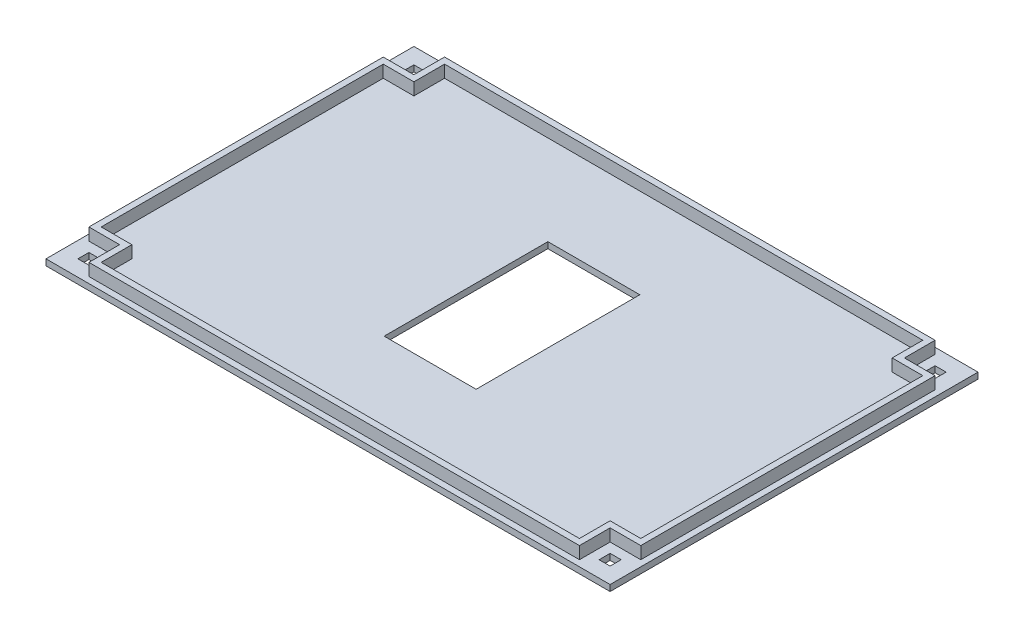
SolidWorks part; units mm, degrees
ref_plane "Спереди" through (0, 0, 0) normal (0, 0, 1) x (1, 0, 0)
ref_plane "Сверху" through (0, 0, 0) normal (0, 1, 0) x (1, 0, 0)
ref_plane "Справа" through (0, 0, 0) normal (1, 0, 0) x (0, 0, -1)
sketch "Эскиз1" plane through (0, 0, 0) normal (0, 1, 0) x (1, 0, 0)
  line L0 (0, 0) -> (92, 0)
  line L1 (0, 0) -> (0, 60)
  line L2 (0, 60) -> (92, 60)
  line L3 (92, 0) -> (92, 60)
  point P4 (0, 0)
  dimension "D1" = 60
  dimension "D2" = 92
extrude "Бобышка-Вытянуть1" add sketch "Эскиз1" along normal blind 1
sketch "Эскиз2" plane through (0, 1, 0) normal (0, 1, 0) x (1, 0, 0)
  line L0 (0, 60) -> (0, 0) construction
  line L1 (91, 1) -> (1, 1)
  line L2 (91, 1) -> (91, 59)
  line L3 (91, 59) -> (1, 59)
  line L4 (1, 1) -> (1, 59)
  line L5 (92, 60) -> (0, 60) construction
  line L6 (92, 0) -> (92, 60) construction
  line L7 (0, 0) -> (92, 0) construction
  line L8 (3.5, 4.4) -> (3.5, 2.6) construction
  line L9 (1, 59) -> (6, 59)
  line L10 (1, 59) -> (1, 54)
  line L11 (1, 54) -> (6, 54)
  line L12 (6, 59) -> (6, 54)
  line L13 (91, 59) -> (86, 59)
  line L14 (91, 59) -> (91, 54)
  line L15 (91, 54) -> (86, 54)
  line L16 (86, 59) -> (86, 54)
  line L17 (91, 1) -> (86, 1)
  line L18 (91, 1) -> (91, 6)
  line L19 (91, 6) -> (86, 6)
  line L20 (86, 1) -> (86, 6)
  line L21 (1, 1) -> (6, 1)
  line L22 (1, 1) -> (1, 6)
  line L23 (1, 6) -> (6, 6)
  line L24 (6, 1) -> (6, 6)
  line L25 (2.6, 57.4) -> (4.4, 57.4)
  line L26 (2.6, 57.4) -> (2.6, 55.6)
  line L27 (2.6, 55.6) -> (4.4, 55.6)
  line L28 (4.4, 57.4) -> (4.4, 55.6)
  line L29 (87.6, 57.4) -> (89.4, 57.4)
  line L30 (87.6, 57.4) -> (87.6, 55.6)
  line L31 (87.6, 55.6) -> (89.4, 55.6)
  line L32 (89.4, 57.4) -> (89.4, 55.6)
  line L33 (87.6, 4.4) -> (89.4, 4.4)
  line L34 (87.6, 4.4) -> (87.6, 2.6)
  line L35 (87.6, 2.6) -> (89.4, 2.6)
  line L36 (89.4, 4.4) -> (89.4, 2.6)
  line L37 (2.6, 4.4) -> (4.4, 4.4)
  line L38 (2.6, 4.4) -> (2.6, 2.6)
  line L39 (2.6, 2.6) -> (4.4, 2.6)
  line L40 (4.4, 4.4) -> (4.4, 2.6)
  line L41 (2.6, 3.5) -> (4.4, 3.5) construction
  line L42 (3.5, 57.4) -> (3.5, 55.6) construction
  line L43 (2.6, 56.5) -> (4.4, 56.5) construction
  line L44 (88.5, 57.4) -> (88.5, 55.6) construction
  line L45 (87.6, 56.5) -> (89.4, 56.5) construction
  line L46 (88.5, 4.4) -> (88.5, 2.6) construction
  line L47 (87.6, 3.5) -> (89.4, 3.5) construction
  line L48 (3.5, 54) -> (3.5, 59) construction
  line L49 (6, 56.5) -> (1, 56.5) construction
  line L50 (86, 56.5) -> (91, 56.5) construction
  line L51 (88.5, 54) -> (88.5, 59) construction
  line L52 (88.5, 6) -> (88.5, 1) construction
  line L53 (86, 3.5) -> (91, 3.5) construction
  line L54 (3.5, 6) -> (3.5, 1) construction
  line L55 (6, 3.5) -> (1, 3.5) construction
  point P72 (0, 0)
  point P73 (0, 0)
  dimension "D1" = 1
  dimension "D2" = 1
  dimension "D3" = 1
  dimension "D4" = 1
  dimension "D5" = 5
  dimension "D6" = 5
  dimension "D7" = 5
  dimension "D8" = 5
  dimension "D9" = 5
  dimension "D10" = 5
  dimension "D11" = 5
  dimension "D12" = 5
  dimension "D13" = 1.8
  dimension "D14" = 1.8
  dimension "D15" = 1.8
  dimension "D16" = 1.8
  dimension "D17" = 1.8
  dimension "D18" = 1.8
  dimension "D19" = 1.8
  dimension "D20" = 1.8
sketch "Эскиз3" plane through (0, 1, 0) normal (0, 1, 0) x (1, 0, 0)
  line L0 (7, 58) -> (7, 53)
  line L1 (7, 53) -> (2, 53)
  line L2 (2, 53) -> (2, 7)
  line L3 (2, 7) -> (7, 7)
  line L4 (7, 7) -> (7, 2)
  line L5 (7, 2) -> (85, 2)
  line L6 (85, 2) -> (85, 7)
  line L7 (85, 7) -> (90, 7)
  line L8 (90, 7) -> (90, 53)
  line L9 (90, 53) -> (85, 53)
  line L10 (85, 53) -> (85, 58)
  line L11 (85, 58) -> (7, 58)
  line L12 (6, 59) -> (6, 54) construction
  line L13 (91, 59) -> (1, 59) construction
  line L14 (1, 1) -> (1, 59) construction
  line L15 (1, 6) -> (6, 6) construction
  line L16 (91, 1) -> (1, 1) construction
  line L17 (86, 1) -> (86, 6) construction
  line L18 (91, 6) -> (86, 6) construction
  line L19 (91, 1) -> (91, 59) construction
  line L20 (91, 54) -> (86, 54) construction
  line L21 (86, 59) -> (86, 54) construction
  line L22 (86, 54) -> (91, 54)
  line L23 (91, 54) -> (91, 6)
  line L24 (91, 6) -> (86, 6)
  line L25 (86, 6) -> (86, 1)
  line L26 (86, 1) -> (6, 1)
  line L27 (6, 1) -> (6, 6)
  line L28 (6, 6) -> (1, 6)
  line L29 (1, 6) -> (1, 54)
  line L30 (1, 54) -> (6, 54)
  line L31 (6, 54) -> (6, 59)
  line L32 (6, 59) -> (86, 59)
  line L33 (86, 59) -> (86, 54)
  dimension "D1" = 1
  dimension "D2" = 1
  dimension "D3" = 1
  dimension "D4" = 1
  dimension "D5" = 1
  dimension "D6" = 1
  dimension "D7" = 1
  dimension "D8" = 1
  dimension "D9" = 1
  dimension "D10" = 1
  dimension "D11" = 1
  dimension "D12" = 1
extrude "Бобышка-Вытянуть3" add sketch "Эскиз3" along normal blind 2
sketch "Эскиз6" plane through (0, 1, 0) normal (0, 1, 0) x (1, 0, 0)
  line L1 (2.6, 57.4) -> (4.4, 57.4)
  line L2 (2.6, 57.4) -> (2.6, 55.6)
  line L3 (2.6, 55.6) -> (4.4, 55.6)
  line L4 (4.4, 57.4) -> (4.4, 55.6)
extrude "Вырез-Вытянуть3" cut sketch "Эскиз6" against normal blind 1
sketch "Эскиз7" plane through (0, 1, 0) normal (0, 1, 0) x (1, 0, 0)
  line L1 (87.6, 57.4) -> (89.4, 57.4)
  line L2 (87.6, 57.4) -> (87.6, 55.6)
  line L3 (87.6, 55.6) -> (89.4, 55.6)
  line L4 (89.4, 57.4) -> (89.4, 55.6)
extrude "Вырез-Вытянуть4" cut sketch "Эскиз7" against normal blind 1
sketch "Эскиз8" plane through (0, 1, 0) normal (0, 1, 0) x (1, 0, 0)
  line L1 (87.6, 4.4) -> (89.4, 4.4)
  line L2 (87.6, 4.4) -> (87.6, 2.6)
  line L3 (87.6, 2.6) -> (89.4, 2.6)
  line L4 (89.4, 4.4) -> (89.4, 2.6)
extrude "Вырез-Вытянуть5" cut sketch "Эскиз8" against normal blind 1
sketch "Эскиз9" plane through (0, 1, 0) normal (0, 1, 0) x (1, 0, 0)
  line L1 (2.6, 4.4) -> (4.4, 4.4)
  line L2 (2.6, 4.4) -> (2.6, 2.6)
  line L3 (2.6, 2.6) -> (4.4, 2.6)
  line L4 (4.4, 4.4) -> (4.4, 2.6)
extrude "Вырез-Вытянуть6" cut sketch "Эскиз9" against normal blind 1
sketch "Эскиз10" plane through (0, 1, 0) normal (0, 1, 0) x (1, 0, 0)
  line L0 (15.0056, 30) -> (25.5056, 30) construction
  line L1 (15.0056, 36) -> (25.5056, 36)
  line L2 (15.0056, 36) -> (15.0056, 24)
  line L3 (15.0056, 24) -> (25.5056, 24)
  line L4 (25.5056, 36) -> (25.5056, 24)
  line L5 (2, 30) -> (90, 30) construction
  line L6 (2, 53) -> (2, 7) construction
  line L7 (90, 7) -> (90, 53) construction
  dimension "D1" = 10.5
  dimension "D2" = 12
sketch "Эскиз11" plane through (0, 1, 0) normal (0, 1, 0) x (1, 0, 0)
  line L0 (73.1241, 37) -> (73.1241, 36) construction
  line L1 (72.1241, 37) -> (74.1241, 37)
  line L2 (72.1241, 37) -> (72.1241, 36)
  line L3 (72.1241, 36) -> (74.1241, 36)
  line L4 (74.1241, 37) -> (74.1241, 36)
  line L5 (70.7241, 30) -> (75.5241, 30) construction
  line L6 (2, 30) -> (90, 30) construction
  circle A0 centre (73.1241, 30) radius 2.4
  dimension "D1" = 4.8
  dimension "D2" = 1
  dimension "D3" = 2
  dimension "D4" = 6
sketch "Эскиз14" plane through (0, 1, 0) normal (0, 1, 0) x (1, 0, 0)
  line L0 (46, 58) -> (46, 2) construction
  line L1 (85, 58) -> (7, 58) construction
  line L2 (7, 2) -> (85, 2) construction
  line L3 (90, 7) -> (90, 53) construction
  line L4 (2, 30) -> (90, 30) construction
  line L5 (2, 53) -> (2, 7) construction
sketch "Эскиз15" plane through (0, 1, 0) normal (0, 1, 0) x (1, 0, 0)
  line L0 (2, 30) -> (90, 30) construction
  line L1 (38.5, 43.35) -> (53.5, 43.35)
  line L2 (38.5, 43.35) -> (38.5, 16.65)
  line L3 (38.5, 16.65) -> (53.5, 16.65)
  line L4 (53.5, 43.35) -> (53.5, 16.65)
  line L5 (38.5, 30) -> (53.5, 30) construction
  line L6 (46, 43.35) -> (46, 16.65) construction
  line L7 (46, 58) -> (46, 2) construction
  dimension "D1" = 15
  dimension "D2" = 26.7
extrude "Вырез-Вытянуть8" cut sketch "Эскиз15" against normal blind 1
